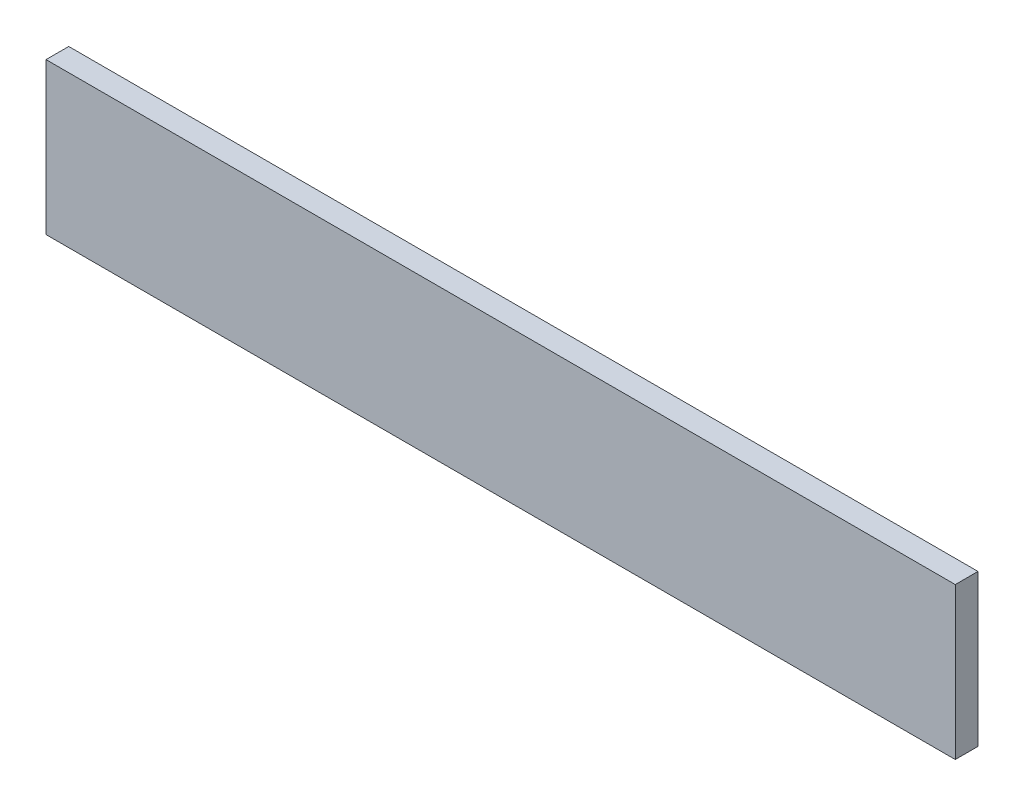
SolidWorks part; units mm, degrees
material "Acrylic (Medium-high impact)"
ref_plane "Front Plane" through (0, 0, 0) normal (0, 0, 1) x (1, 0, 0)
ref_plane "Top Plane" through (0, 0, 0) normal (0, 1, 0) x (1, 0, 0)
ref_plane "Right Plane" through (0, 0, 0) normal (1, 0, 0) x (0, 0, -1)
sketch "Sketch1" plane through (0, 0, 0) normal (0, 0, 1) x (1, 0, 0)
  line L1 (60, -10) -> (-60, -10)
  line L2 (60, -10) -> (60, 10)
  line L3 (60, 10) -> (-60, 10)
  line L4 (-60, -10) -> (-60, 10)
  line L5 (60, -10) -> (-60, 10) construction
  line L6 (60, 10) -> (-60, -10) construction
  point P0 (0, 0)
  dimension "D1" = 20
  dimension "D2" = 120
extrude "Boss-Extrude1" add sketch "Sketch1" along normal blind 3
equation "\"L\"= 120"
equation "\"D2@Sketch1\"=\"L\""
